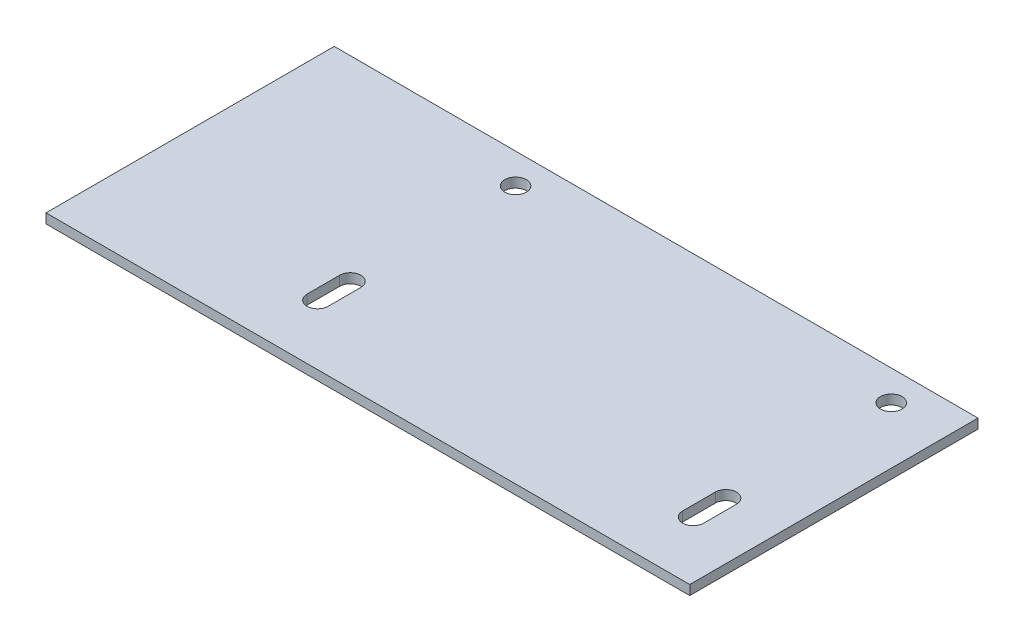
SolidWorks part; units mm, degrees
ref_plane "Front Plane" through (0, 0, 0) normal (0, 0, 1) x (1, 0, 0)
ref_plane "Top Plane" through (0, 0, 0) normal (0, 1, 0) x (1, 0, 0)
ref_plane "Right Plane" through (0, 0, 0) normal (1, 0, 0) x (0, 0, -1)
sketch "Sketch1" plane through (0, 0, 0) normal (0, 1, 0) x (1, 0, 0)
  line L1 (-167.5, -75) -> (167.5, -75)
  line L2 (-167.5, -75) -> (-167.5, 75)
  line L3 (-167.5, 75) -> (167.5, 75)
  line L4 (167.5, -75) -> (167.5, 75)
  line L5 (-167.5, -75) -> (167.5, 75) construction
  line L6 (-167.5, 75) -> (167.5, -75) construction
  point P0 (0, 0)
  dimension "D1" = 150
  dimension "D2" = 335
extrude "Boss-Extrude1" add sketch "Sketch1" along normal blind 5
sketch "Sketch2" plane through (0, 5, 0) normal (0, 1, 0) x (1, 0, 0)
  line L0 (137.99, -26.69) -> (137.99, -43.69) construction
  line L1 (143.49, -26.69) -> (143.49, -43.69)
  line L2 (132.49, -26.69) -> (132.49, -43.69)
  line L3 (167.5, 75) -> (-167.5, 75) construction
  line L4 (167.5, -75) -> (167.5, 75) construction
  line L5 (-167.5, -75) -> (167.5, -75) construction
  line L6 (-57.46, -26.69) -> (-57.46, -43.69) construction
  line L7 (-51.96, -26.69) -> (-51.96, -43.69)
  line L8 (-62.96, -26.69) -> (-62.96, -43.69)
  arc A0 (143.49, -26.69) -> (132.49, -26.69) centre (137.99, -26.69) ccw
  arc A1 (132.49, -43.69) -> (143.49, -43.69) centre (137.99, -43.69) ccw
  arc A2 (-51.96, -26.69) -> (-62.96, -26.69) centre (-57.46, -26.69) ccw
  arc A3 (-62.96, -43.69) -> (-51.96, -43.69) centre (-57.46, -43.69) ccw
  circle A4 centre (138.025, 59.315) radius 5.625
  circle A5 centre (-57.465, 59.315) radius 5.625
  point P2 (137.99, -35.19)
  point P8 (137.99, -49.19)
  point P15 (-57.46, -35.19)
  dimension "D4" = 29.475
  dimension "D7" = 25.81
  dimension "D3" = 11.25
  dimension "D6" = 15.685
  dimension "D10" = 11.25
  dimension "D12" = 224.965
  dimension "D13" = 15.685
  dimension "D1" = 11
  dimension "D2" = 17
  dimension "D5" = 24.01
  dimension "D8" = 11
  dimension "D9" = 17
  dimension "D11" = 219.46
extrude "Cut-Extrude1" cut sketch "Sketch2" against normal blind 10
